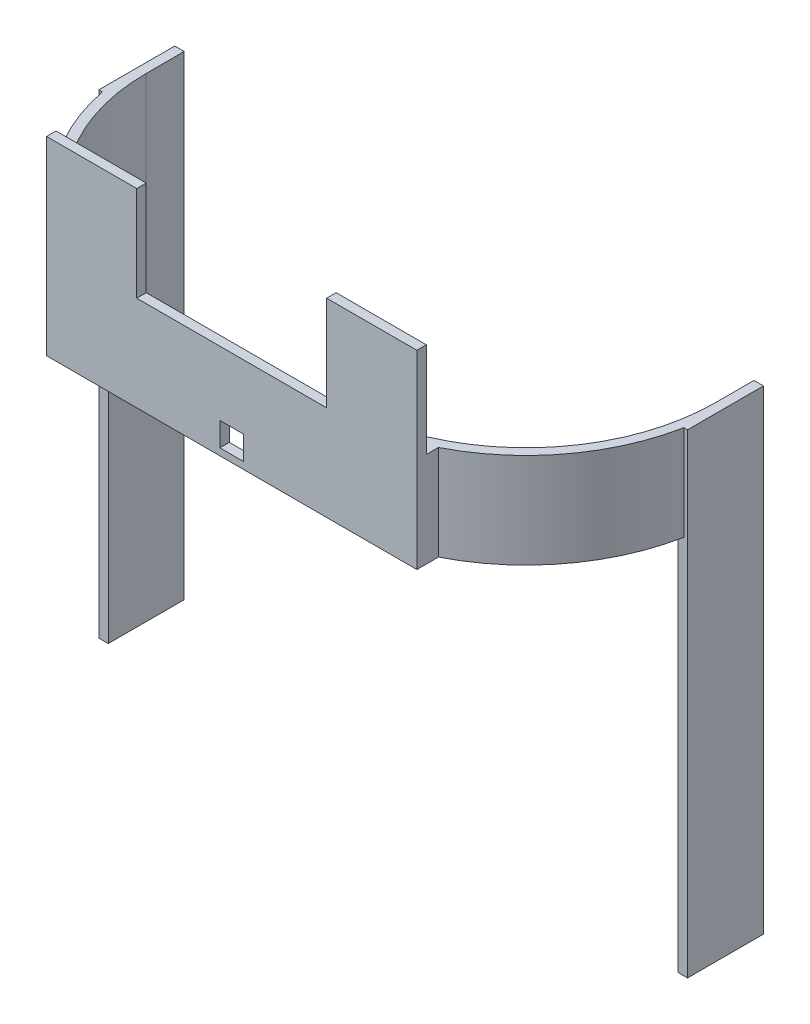
SolidWorks part; units mm, degrees
ref_plane "Front" through (0, 0, 0) normal (0, 0, 1) x (1, 0, 0)
ref_plane "Top" through (0, 0, 0) normal (0, 1, 0) x (1, 0, 0)
ref_plane "Right" through (0, 0, 0) normal (1, 0, 0) x (0, 0, -1)
sketch "草图2" plane through (0, 0, 0) normal (0, 1, 0) x (1, 0, 0)
  line L0 (-0.7345, 0) -> (19.6327, 0) construction
  line L2 (-40, -80) -> (40, -80)
  line L3 (-0.7345, 0) -> (19.6327, 0) construction
  line L5 (-40, -84) -> (40, -84)
  line L7 (-124, 16) -> (-120, 16)
  line L10 (-124, 16) -> (-124, -16)
  line L11 (-124, -16) -> (-122.4621, -16)
  line L12 (-120, 16) -> (-120, 0)
  line L13 (120, 16) -> (124, 16)
  line L14 (120, 16) -> (120, 0)
  line L15 (122.4621, -16) -> (124, -16)
  line L16 (124, 16) -> (124, -16)
  arc A0 (-120, 0) -> (-40, -80) centre (-40, 0) ccw
  arc A1 (40, -80) -> (120, 0) centre (40, 0) ccw
  arc A2 (-122.4621, -16) -> (-40, -84) centre (-40, 0) ccw
  arc A3 (40, -84) -> (122.4621, -16) centre (40, 0) ccw
  point P2 (0, 0)
  point P9 (9.4491, 0)
  dimension "D1" = 32
  dimension "D3" = 32
extrude "凸台-拉伸1" add sketch "草图2" along normal blind 40
sketch "草图3" plane through (0, 0, 0) normal (0, -1, 0) x (1, 0, 0)
  line L1 (-124, -16) -> (-120, -16)
  line L2 (-124, -16) -> (-124, 16)
  line L3 (-124, 16) -> (-120, 16)
  line L4 (-120, -16) -> (-120, 16)
  line L5 (120, -16) -> (124, -16)
  line L6 (120, -16) -> (120, 16)
  line L7 (120, 16) -> (124, 16)
  line L8 (124, -16) -> (124, 16)
extrude "凸台-拉伸2" add sketch "草图3" along normal blind 160
sketch "草图5" plane through (0, 40, 0) normal (0, 1, 0) x (1, 0, 0)
  line L0 (-40, -84) -> (-78, -84)
  line L1 (-78, -84) -> (-78, -74.9133)
  line L2 (40, -84) -> (78, -84)
  line L3 (78, -84) -> (78, -72.6077)
  line L4 (-40, -84) -> (40, -84)
  line L5 (78, -72.6077) -> (52.8973, -80.9462)
  line L6 (52.8973, -80.9462) -> (-55.5335, -80.9462)
  line L7 (-55.5335, -80.9462) -> (-78, -74.9133)
extrude "凸台-拉伸3" add sketch "草图5" against normal blind 40
sketch "草图6" plane through (0, 40, 0) normal (0, 1, 0) x (1, 0, 0)
  line L1 (-78, -84) -> (-40, -84)
  line L2 (-78, -84) -> (-78, -80)
  line L3 (-78, -80) -> (-40, -80)
  line L4 (-40, -84) -> (-40, -80)
  line L5 (78, -84) -> (40, -84)
  line L6 (78, -84) -> (78, -80)
  line L7 (78, -80) -> (40, -80)
  line L8 (40, -84) -> (40, -80)
extrude "凸台-拉伸4" add sketch "草图6" along normal blind 40
sketch "草图4" plane through (0, 0, 84) normal (0, 0, 1) x (1, 0, 0)
  line L0 (0, 7.906) -> (0, 12.5771) construction
  line L1 (0, 7.906) -> (5.1057, 7.906) construction
  line L3 (-5, 12.906) -> (5, 12.906)
  line L4 (-5, 12.906) -> (-5, 2.906)
  line L5 (-5, 2.906) -> (5, 2.906)
  line L6 (5, 12.906) -> (5, 2.906)
  dimension "D1" = 10
  dimension "D2" = 10
  dimension "D3" = 5
  dimension "D4" = 5
extrude "切除-拉伸1" cut sketch "草图4" against normal through all both and the other way through all
